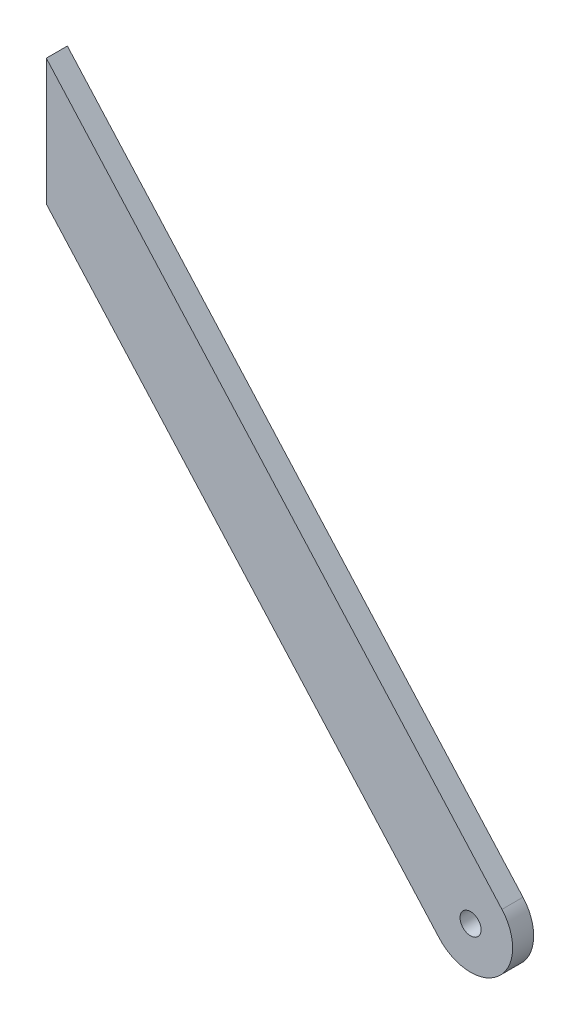
SolidWorks part; units mm, degrees
ref_plane "Front Plane" through (0, 0, 0) normal (0, 0, 1) x (1, 0, 0)
ref_plane "Top Plane" through (0, 0, 0) normal (0, 1, 0) x (1, 0, 0)
ref_plane "Right Plane" through (0, 0, 0) normal (1, 0, 0) x (0, 0, -1)
sketch "Sketch1" plane through (0, 0, 0) normal (0, 0, 1) x (1, 0, 0)
  line L0 (0, 0) -> (0, 60)
  line L1 (0, 60) -> (216.4809, -182.033)
  line L3 (186.6667, -208.6997) -> (0, 0)
  arc A0 (216.4809, -182.033) -> (186.6667, -208.6997) centre (201.5738, -195.3663) cw
  circle A1 centre (201.5738, -195.3663) radius 5
  dimension "D3" = 10
  dimension "D4" = 20
  dimension "D1" = 60
  dimension "D2" = 280
extrude "Boss-Extrude1" add sketch "Sketch1" along normal blind 10
